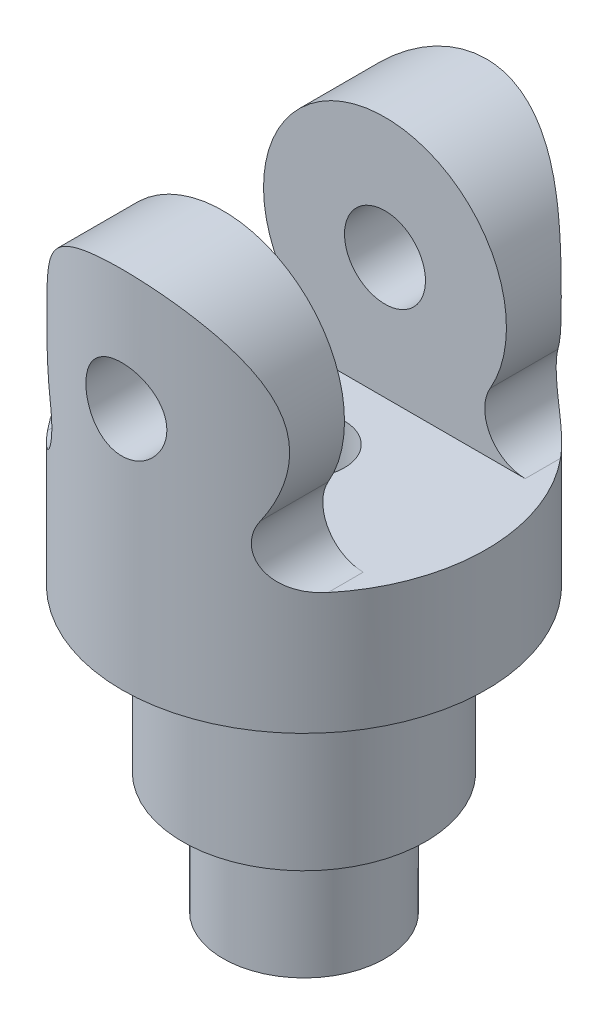
SolidWorks part; units mm, degrees
ref_plane "Front Plane" through (0, 0, 0) normal (0, 0, 1) x (1, 0, 0)
ref_plane "Top Plane" through (0, 0, 0) normal (0, 1, 0) x (1, 0, 0)
ref_plane "Right Plane" through (0, 0, 0) normal (1, 0, 0) x (0, 0, -1)
sketch "Sketch1" plane through (0, 0, 0) normal (0, 0, 1) x (1, 0, 0)
  line L0 (10, 0) -> (20, 0)
  line L1 (20, 0) -> (20, 30)
  line L2 (20, 30) -> (30, 30)
  line L3 (30, 30) -> (30, 70)
  line L4 (30, 70) -> (45, 70)
  line L5 (45, 70) -> (45, 160)
  line L6 (45, 160) -> (10, 160)
  line L7 (10, 160) -> (10, 0)
  line L8 (0, 0) -> (0, 109.981) construction
  dimension "D1" = 160
  dimension "D2" = 10
  dimension "D3" = 20
  dimension "D4" = 30
  dimension "D5" = 45
  dimension "D6" = 30
  dimension "D7" = 40
revolve "Revolve1" add sketch "Sketch1" angle 360 about L8
sketch "Sketch2" plane through (0, 0, 0) normal (0, 0, 1) x (1, 0, 0)
  line L6 (45, 160) -> (-45, 160) construction
  line L8 (-34.641, 100) -> (-50, 100)
  line L9 (-50, 100) -> (-50, 160)
  line L10 (-50, 160) -> (0, 160)
  arc A2 (0, 160) -> (-25.9808, 115) centre (0, 130) ccw
  arc A3 (-34.641, 100) -> (-25.9808, 115) centre (-34.641, 110) ccw
  dimension "D1" = 60
  dimension "D2" = 50
  dimension "D3" = 20
  dimension "D4" = 50
extrude "Cut-Extrude1" cut sketch "Sketch2" against normal through all both and the other way through all
mirror "Mirror1" about plane through (0, 0, 0) normal (1, 0, 0) of "Cut-Extrude1"
sketch "Sketch3" plane through (0, 0, 0) normal (1, 0, 0) x (0, 0, -1)
  line L0 (-10, 160) -> (-45, 160) construction
  line L1 (-20, 160) -> (20, 160)
  line L2 (-20, 160) -> (-20, 100)
  line L3 (-20, 100) -> (20, 100)
  line L4 (20, 160) -> (20, 100)
  line L5 (28.7228, 100) -> (-28.7228, 100) construction
  line L6 (0, 0) -> (0, 128.3019) construction
  dimension "D1" = 40
extrude "Cut-Extrude2" cut sketch "Sketch3" against normal through all both and the other way through all
sketch "Sketch5" plane through (0, 0, 0) normal (0, 0, 1) x (1, 0, 0)
  circle A0 centre (0, 130) radius 10
  dimension "D1" = 20
extrude "Cut-Extrude3" cut sketch "Sketch5" against normal through all both and the other way through all
